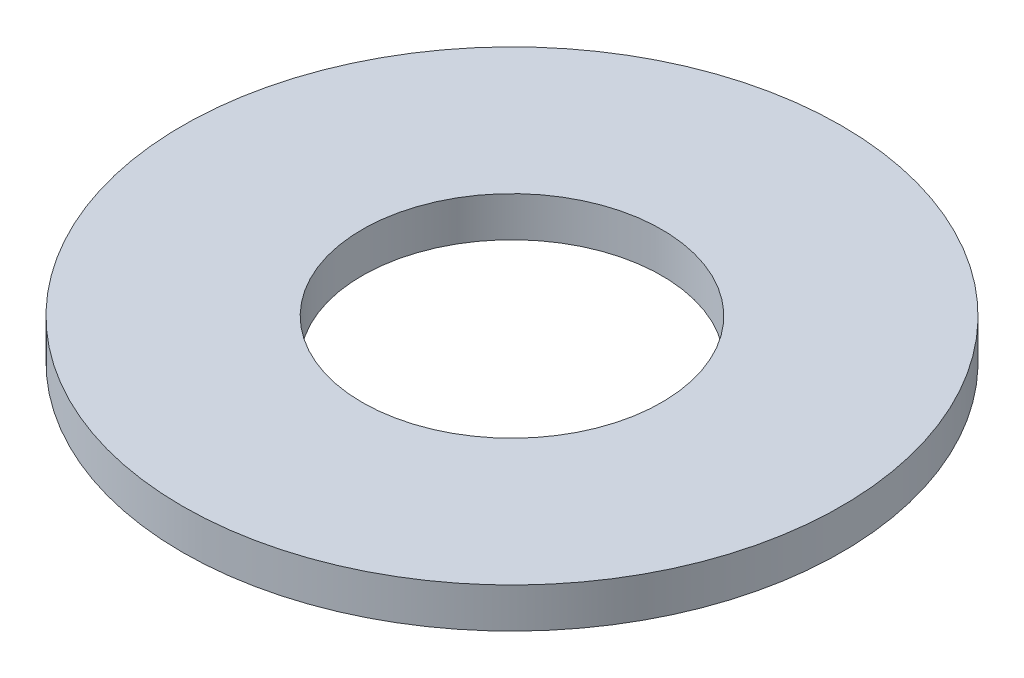
SolidWorks part; units mm, degrees
ref_plane "Front Plane" through (0, 0, 0) normal (0, 0, 1) x (1, 0, 0)
ref_plane "Top Plane" through (0, 0, 0) normal (0, 1, 0) x (1, 0, 0)
ref_plane "Right Plane" through (0, 0, 0) normal (1, 0, 0) x (0, 0, -1)
sketch "Sketch1" plane through (0, 0, 0) normal (0, 1, 0) x (1, 0, 0)
  circle A0 centre (0, 0) radius 82.5
  circle A1 centre (0, 0) radius 37.5
  dimension "D1" = 75
  dimension "D2" = 165
extrude "Boss-Extrude1" add sketch "Sketch1" along normal blind 10
